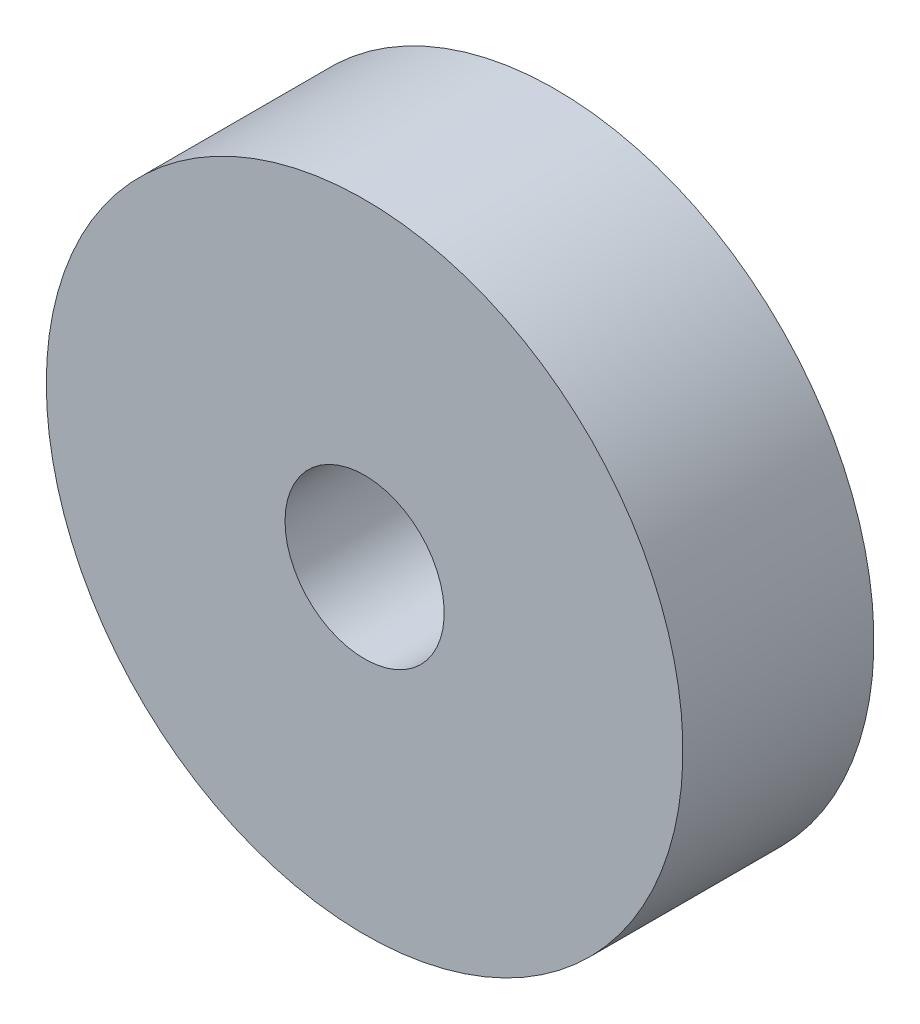
SolidWorks part; units mm, degrees
ref_plane "Front Plane" through (0, 0, 0) normal (1, 0, 0) x (0, 1, 0)
ref_plane "Top Plane" through (0, 0, 0) normal (0, 0, 1) x (0, 1, 0)
ref_plane "Right Plane" through (0, 0, 0) normal (0, 1, 0) x (-1, 0, 0)
sketch "Sketch1" plane through (0, 0, 0) normal (0, 0, 1) x (0, 1, 0)
  circle A0 centre (0, 0) radius 3.9688
  circle A1 centre (0, 0) radius 15.875
  dimension "D1" = 7.9375
  dimension "D2" = 31.75
extrude "Boss-Extrude1" add sketch "Sketch1" along normal blind 9.525
